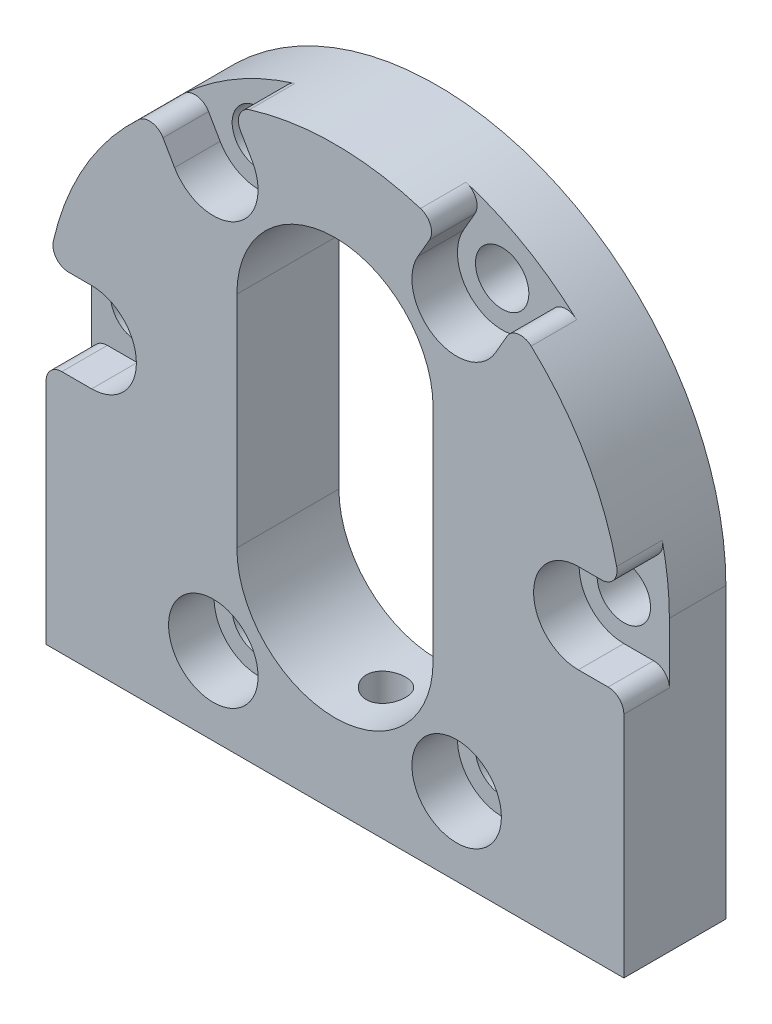
SolidWorks part; units mm, degrees
ref_plane "Front Plane" through (0, 0, 0) normal (0, 0, 1) x (1, 0, 0)
ref_plane "Top Plane" through (0, 0, 0) normal (0, 1, 0) x (1, 0, 0)
ref_plane "Right Plane" through (0, 0, 0) normal (1, 0, 0) x (0, 0, -1)
sketch "Sketch1" plane through (0, 0, 0) normal (0, 0, 1) x (1, 0, 0)
  line L0 (-18.4, 18.4) -> (-18.4, 0)
  line L1 (-18.4, 0) -> (18.4, 0)
  line L2 (18.4, 0) -> (18.4, 18.4)
  line L3 (0, 25.4) -> (0, 11.4) construction
  line L4 (6.25, 25.4) -> (6.25, 11.4)
  line L5 (-6.25, 25.4) -> (-6.25, 11.4)
  arc A0 (18.4, 18.4) -> (-18.4, 18.4) centre (0, 18.4) ccw
  arc A1 (6.25, 25.4) -> (-6.25, 25.4) centre (0, 25.4) ccw
  arc A2 (-6.25, 11.4) -> (6.25, 11.4) centre (0, 11.4) ccw
  point P8 (0, 18.4)
  dimension "D1" = 36.8
  dimension "D2" = 12.5
  dimension "D3" = 14
  dimension "D4" = 5.15
extrude "Boss-Extrude1" add sketch "Sketch1" along normal mid plane 6.5
sketch "Sketch2" plane through (0, 0, 3.25) normal (0, 0, 1) x (1, 0, 0)
  line L1 (15.5, 18.4) -> (7.75, 31.8234)
  line L2 (7.75, 31.8234) -> (-7.75, 31.8234)
  line L3 (-7.75, 31.8234) -> (-15.5, 18.4)
  line L4 (-15.5, 18.4) -> (-7.75, 4.9766)
  line L5 (-7.75, 4.9766) -> (7.75, 4.9766)
  line L6 (7.75, 4.9766) -> (15.5, 18.4)
  circle A0 centre (0, 18.4) radius 15.5
  circle A1 centre (0, 18.4) radius 13.4234 construction
  dimension "D1" = 31
hole_wizard "CBORE for M3 SBHCS1" positions "Sketch3" profile "Sketch5" counterbore size "M3" standard "ANSI Metric" end condition through all
sketch "Sketch3" plane through (0, 0, 3.25) normal (0, 0, 1) x (1, 0, 0)
  point P0 (7.75, 4.9766)
  point P3 (15.5, 18.4)
  point P6 (7.75, 31.8234)
  point P9 (-7.75, 31.8234)
  point P12 (-15.5, 18.4)
  point P15 (-7.75, 4.9766)
sketch "Sketch5" plane through (7.75, 4.9766, 3.25) normal (1, 0, 0) x (0, -1, 0)
  line L0 (0, 0) -> (0, 6.5)
  line L1 (0, 6.5) -> (1.7, 6.5)
  line L3 (1.7, 6.5) -> (1.7, 2.9)
  line L4 (1.7, 2.9) -> (2.85, 2.9)
  line L5 (2.85, 2.9) -> (2.85, 0)
  line L7 (2.85, 0) -> (0, 0)
  line L11 (0, -6.35) -> (0, 107.95) construction
  dimension "Thru Hole Dia." = 3.4
  dimension "Thru Hole Depth" = 6.5
  dimension "C'Bore Dia." = 5.7
  dimension "C'Bore Depth" = 2.9
sketch "Sketch6" plane through (0, 0, 0.35) normal (0, 0, 1) x (1, 0, 0)
  line L0 (-18.4, 18.4) -> (-18.4, 0) construction
  line L1 (-15.5, 21.25) -> (-18.4, 21.25)
  line L2 (-15.5, 21.25) -> (-15.5, 15.55)
  line L3 (-15.5, 15.55) -> (-18.4, 15.55)
  line L4 (-18.4, 21.25) -> (-18.4, 15.55)
  line L5 (18.4, 0) -> (18.4, 18.4) construction
  line L6 (15.5, 21.25) -> (18.4, 21.25)
  line L7 (15.5, 21.25) -> (15.5, 15.55)
  line L8 (15.5, 15.55) -> (18.4, 15.55)
  line L9 (18.4, 21.25) -> (18.4, 15.55)
  line L10 (-7.75, 31.8234) -> (0, 18.4) construction
  line L11 (0, 18.4) -> (7.75, 31.8234) construction
  line L12 (-10.2182, 30.3984) -> (-11.6747, 32.9212)
  line L13 (-11.6747, 32.9212) -> (-6.7255, 35.7489)
  line L14 (-6.7255, 35.7489) -> (-5.2818, 33.2484)
  line L15 (-5.2818, 33.2484) -> (-10.2182, 30.3984)
  line L16 (5.2818, 33.2484) -> (6.7318, 35.7599)
  line L17 (6.7318, 35.7599) -> (11.6682, 32.9099)
  line L18 (11.6682, 32.9099) -> (10.2182, 30.3984)
  line L19 (10.2182, 30.3984) -> (5.2818, 33.2484)
  circle A0 centre (-15.5, 18.4) radius 2.85 construction
  circle A1 centre (-15.5, 18.4) radius 2.85 construction
  circle A2 centre (15.5, 18.4) radius 2.85 construction
  circle A3 centre (15.5, 18.4) radius 2.85 construction
  circle A4 centre (-7.75, 31.8234) radius 2.85 construction
  circle A5 centre (-7.75, 31.8234) radius 2.85 construction
  circle A6 centre (7.75, 31.8234) radius 2.85 construction
  circle A7 centre (7.75, 31.8234) radius 2.85 construction
  arc A8 (18.4, 18.4) -> (-18.4, 18.4) centre (0, 18.4) ccw construction
extrude "Cut-Extrude1" cut sketch "Sketch6" along normal through all
sketch "Sketch7" plane through (0, 0, 0) normal (0, -1, 0) x (1, 0, 0)
  line L0 (-18.4, 0) -> (18.4, 0) construction
  line L1 (-18.4, 3.25) -> (-18.4, -3.25) construction
  line L2 (18.4, 3.25) -> (18.4, -3.25) construction
  point P6 (0, 0)
  point P7 (14.8, 0)
  point P9 (-14.8, 0)
  dimension "D1" = 14.8
  dimension "D2" = 14.8
  dimension "D3" = 3.6
hole_wizard "M3x0.5 Tapped Hole1" positions "Sketch8" profile "Sketch9" tap size "M3x0.5" standard "ANSI Metric"
sketch "Sketch8" plane through (0, 0, 0) normal (0, -1, 0) x (-1, 0, 0)
  point P0 (14.8, 0)
  point P3 (0, 0)
  point P6 (-14.8, 0)
sketch "Sketch9" plane through (-14.8, 0, 0) normal (1, 0, 0) x (0, 0, -1)
  line L0 (0, 0) -> (0, 8.7511)
  line L1 (0, 8.7511) -> (1.25, 8)
  line L2 (1.25, 8) -> (1.25, 0)
  line L5 (1.25, 0) -> (0, 0)
  line L10 (0, 8.7511) -> (-1.25, 8) construction
  line L11 (0, -6.35) -> (0, 107.95) construction
  dimension "Tap Drill Dia." = 2.5
  dimension "Tap Drill Depth" = 8
  dimension "Drill Angle" = 118
cosmetic thread "Hole Thread1" parameters "D1"=6.5, "D2"=3
cosmetic thread "Hole Thread2" parameters "D1"=5.2763, "D2"=3
cosmetic thread "Hole Thread3" parameters "D1"=6.5, "D2"=3
fillet "Fillet1" radius 1 8 edges at (-18.4, 15.55, 1.8) (-18.1779, 21.25, 1.8) (-11.5571, 32.7176, 1.8) (-6.6208, 35.5676, 1.8) (6.6208, 35.5676, 1.8) (11.5571, 32.7176, 1.8) (18.1779, 21.25, 1.8) (18.4, 15.55, 1.8)
